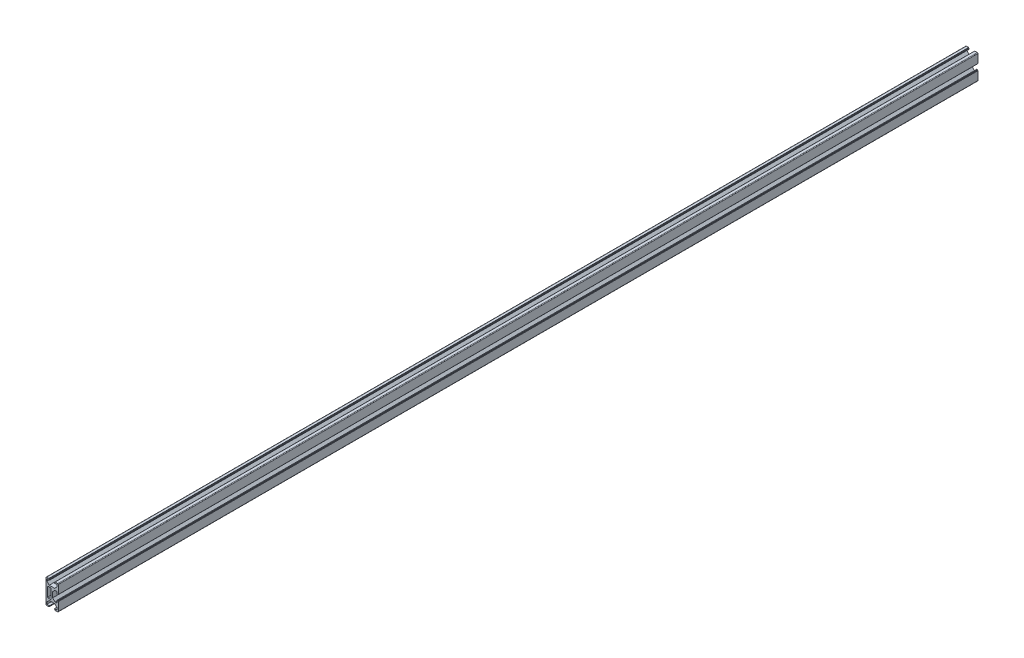
SolidWorks part; units mm, degrees
ref_plane "前视基准面" through (0, 0, 0) normal (0, 0, 1) x (1, 0, 0)
ref_plane "上视基准面" through (0, 0, 0) normal (0, 1, 0) x (1, 0, 0)
ref_plane "右视基准面" through (0, 0, 0) normal (1, 0, 0) x (0, 0, -1)
sketch "草图30" plane through (0, 0, 0) normal (0, 0, 1) x (1, 0, 0)
  line L0 (-10, 8.9627) -> (10, 8.9627) construction
  point P2 (0, 8.9627)
  line B0 (-1.7, 7.3) -> (-1.7, -7.3)
  line B1 (-2.7, -8.3) -> (-6.5, -8.3)
  line B2 (-7.5, -7.3) -> (-7.5, 7.3)
  line B3 (-6.5, 8.3) -> (-2.7, 8.3)
  line B4 (0.8, 4.3858) -> (4.6642, 8.25)
  line B5 (4.6642, 8.25) -> (8, 8.25)
  line B6 (8, 8.25) -> (8, 4.1)
  line B7 (8, 4.1) -> (9.2, 4.1)
  line B8 (9.2, 4.1) -> (9.2, 5.1)
  line B9 (9.2, 5.1) -> (10, 5.1)
  line B10 (10, 5.1) -> (10, 19)
  line B11 (9, 20) -> (4.8784, 20)
  line B12 (4.8784, 20) -> (4.8784, 19.2)
  line B13 (4.8784, 19.2) -> (3.8784, 19.2)
  line B14 (3.8784, 19.2) -> (3.8784, 18)
  line B15 (3.8784, 18) -> (8.0284, 18)
  line B16 (8.0284, 18) -> (8.0284, 14.6642)
  line B17 (8.0284, 14.6642) -> (4.1642, 10.8)
  line B18 (4.1642, 10.8) -> (-4.6074, 10.8)
  line B19 (-4.6074, 10.8) -> (-8.4716, 14.6642)
  line B20 (-8.4716, 14.6642) -> (-8.4716, 18)
  line B21 (-8.4716, 18) -> (-4.3216, 18)
  line B22 (-4.3216, 18) -> (-4.3216, 19.2)
  line B23 (-4.3216, 19.2) -> (-5.3216, 19.2)
  line B24 (-5.3216, 19.2) -> (-5.3216, 20)
  line B25 (-5.3216, 20) -> (-9, 20)
  line B26 (-10, 19) -> (-10, -19)
  line B27 (-9, -20) -> (-5.3216, -20)
  line B28 (-5.3216, -20) -> (-5.3216, -19.2)
  line B29 (-5.3216, -19.2) -> (-4.3216, -19.2)
  line B30 (-4.3216, -19.2) -> (-4.3216, -18)
  line B31 (-4.3216, -18) -> (-8.4716, -18)
  line B32 (-8.4716, -18) -> (-8.4716, -14.6642)
  line B33 (-8.4716, -14.6642) -> (-4.6074, -10.8)
  line B34 (-4.6074, -10.8) -> (4.1642, -10.8)
  line B35 (4.1642, -10.8) -> (8.0284, -14.6642)
  line B36 (8.0284, -14.6642) -> (8.0284, -18)
  line B37 (8.0284, -18) -> (3.8784, -18)
  line B38 (3.8784, -18) -> (3.8784, -19.2)
  line B39 (3.8784, -19.2) -> (4.8784, -19.2)
  line B40 (4.8784, -19.2) -> (4.8784, -20)
  line B41 (4.8784, -20) -> (9, -20)
  line B42 (10, -19) -> (10, -5.1)
  line B43 (10, -5.1) -> (9.2, -5.1)
  line B44 (9.2, -5.1) -> (9.2, -4.1)
  line B45 (9.2, -4.1) -> (8, -4.1)
  line B46 (8, -4.1) -> (8, -8.25)
  line B47 (8, -8.25) -> (4.6642, -8.25)
  line B48 (4.6642, -8.25) -> (0.8, -4.3858)
  line B49 (0.8, -4.3858) -> (0.8, 4.3858)
  arc B50 (-1.7, 7.3) -> (-2.7, 8.3) centre (-2.7, 7.3) ccw
  arc B51 (-2.7, -8.3) -> (-1.7, -7.3) centre (-2.7, -7.3) ccw
  arc B52 (-7.5, -7.3) -> (-6.5, -8.3) centre (-6.5, -7.3) ccw
  arc B53 (-6.5, 8.3) -> (-7.5, 7.3) centre (-6.5, 7.3) ccw
  arc B54 (10, 19) -> (9, 20) centre (9, 19) ccw
  arc B55 (-9, 20) -> (-10, 19) centre (-9, 19) ccw
  arc B56 (-10, -19) -> (-9, -20) centre (-9, -19) ccw
  arc B57 (9, -20) -> (10, -19) centre (9, -19) ccw
sketch_block_instance "块2-1"
sketch_block "块2"
extrude "凸台-拉伸3" add sketch "草图30" along normal blind 1500
ref_plane "基准面1" through (0, 0, 50) normal (0, 0, 1) x (1, 0, 0)
ref_plane "基准面2" through (0, 20, 0) normal (0, 1, 0) x (1, 0, 0)
ref_plane "基准面3" through (0, -20, 0) normal (0, 1, 0) x (1, 0, 0)
ref_plane "基准面4" through (10, 0, 0) normal (1, 0, 0) x (0, 0, -1)
ref_plane "基准面5" through (-10, 0, 0) normal (1, 0, 0) x (0, 0, -1)
sketch "草图19" plane through (0, 0, 0) normal (0, 0, 1) x (1, 0, 0)
  line L0 (0, 0) -> (0, 11.6901) construction
  line L1 (0, 0) -> (10.3437, 0) construction
sketch "草图20" plane through (0, 0, 0) normal (0, 1, 0) x (1, 0, 0)
  line L0 (0, 0) -> (0, 3.5576) construction
ref_point "点1"
sketch "草图2" [suppressed] plane through (0, 0, 0) normal (1, 0, 0) x (0, 0, -1)
  line L0 (-370, -20) -> (-330, 20)
  line L1 (11.189, -20) -> (-11.189, -20) construction
  line L2 (11.189, 20) -> (-11.189, 20) construction
  line L3 (-330, 20) -> (-370, 20)
  line L4 (-370, 11.189) -> (-370, -11.189) construction
  line L5 (-370, 20) -> (-370, -20)
  dimension "D1" = 45
extrude "切除-拉伸1" [suppressed] cut sketch "草图2" against normal through all and the other way through all
sketch "草图3" [suppressed] plane through (0, 0, 0) normal (1, 0, 0) x (0, 0, -1)
  line L0 (0, -20) -> (-40, 20)
  line L1 (11.189, -20) -> (-11.189, -20) construction
  line L2 (11.189, 20) -> (-11.189, 20) construction
  line L3 (-40, 20) -> (0, 20)
  line L4 (0, 20) -> (0, -20)
  line L5 (0, 11.189) -> (0, -11.189) construction
  dimension "D1" = 45
extrude "切除-拉伸2" [suppressed] cut sketch "草图3" against normal through all and the other way through all
sketch "草图4" [suppressed] plane through (0, 0, 0) normal (1, 0, 0) x (0, 0, -1)
  line L0 (-370, 20) -> (-330, -20)
  line L1 (11.189, 20) -> (-11.189, 20) construction
  line L2 (-370, 11.189) -> (-370, -11.189) construction
  line L3 (11.189, -20) -> (-11.189, -20) construction
  line L4 (-330, -20) -> (-370, -20)
  line L5 (-370, -20) -> (-370, 20)
  dimension "D1" = 45
extrude "切除-拉伸3" [suppressed] cut sketch "草图4" against normal through all and the other way through all
sketch "草图5" [suppressed] plane through (0, 0, 0) normal (1, 0, 0) x (0, 0, -1)
  line L0 (0, 20) -> (-40, -20)
  line L1 (11.189, 20) -> (-11.189, 20) construction
  line L2 (11.189, -20) -> (-11.189, -20) construction
  line L3 (-40, -20) -> (0, -20)
  line L4 (0, -20) -> (0, 20)
  line L5 (0, 11.189) -> (0, -11.189) construction
  dimension "D1" = 45
extrude "切除-拉伸4" [suppressed] cut sketch "草图5" against normal through all and the other way through all
sketch "草图6" [suppressed] plane through (0, 0, 0) normal (0, 1, 0) x (1, 0, 0)
  line L0 (-10, -370) -> (10, -350)
  line L1 (-10, -22) -> (-10, 22) construction
  line L2 (-11.189, -370) -> (11.189, -370) construction
  line L3 (10, -22) -> (10, 22) construction
  line L4 (10, -350) -> (10, -370)
  line L5 (10, -370) -> (-10, -370)
  dimension "D1" = 45
extrude "切除-拉伸5" [suppressed] cut sketch "草图6" against normal through all and the other way through all
sketch "草图7" [suppressed] plane through (0, 0, 0) normal (0, 1, 0) x (1, 0, 0)
  line L0 (-10, 0) -> (10, -20)
  line L1 (-10, -22) -> (-10, 22) construction
  line L2 (10, -22) -> (10, 22) construction
  line L3 (10, -20) -> (10, 0)
  line L4 (-11.189, 0) -> (11.189, 0) construction
  line L5 (10, 0) -> (-10, 0)
  dimension "D1" = 45
extrude "切除-拉伸6" [suppressed] cut sketch "草图7" against normal through all and the other way through all
sketch "草图8" [suppressed] plane through (0, 0, 0) normal (0, 1, 0) x (1, 0, 0)
  line L0 (-10, -350) -> (10, -370)
  line L1 (-10, -22) -> (-10, 22) construction
  line L2 (10, -22) -> (10, 22) construction
  line L3 (-11.189, -370) -> (11.189, -370) construction
  line L4 (10, -370) -> (-10, -370)
  line L5 (-10, -370) -> (-10, -350)
  dimension "D1" = 45
extrude "切除-拉伸7" [suppressed] cut sketch "草图8" against normal through all and the other way through all
sketch "草图9" [suppressed] plane through (0, 0, 0) normal (0, 1, 0) x (1, 0, 0)
  line L0 (10, 0) -> (-10, -20)
  line L1 (10, -22) -> (10, 22) construction
  line L2 (-11.189, 0) -> (11.189, 0) construction
  line L3 (-10, -22) -> (-10, 22) construction
  line L4 (-10, -20) -> (-10, 0)
  line L5 (-10, 0) -> (10, 0)
  dimension "D1" = 45
extrude "切除-拉伸8" [suppressed] cut sketch "草图9" against normal through all and the other way through all
sketch "草图18" [suppressed] plane through (0, 0, 0) normal (0, 1, 0) x (1, 0, 0)
  line L0 (-10, -307) -> (10, -307)
  line L1 (-10, -22) -> (-10, 22) construction
  line L2 (10, -22) -> (10, 22) construction
  line L3 (10, -307) -> (10, -300)
  line L4 (10, -300) -> (1.5, -300)
  line L5 (1.5, -300) -> (1.5, -302.5)
  line L6 (1.5, -302.5) -> (-10, -302.5)
  line L7 (-10, -302.5) -> (-10, -307)
  line L8 (-11.189, -370) -> (11.189, -370) construction
  dimension "D1" = 63
  dimension "D2" = 7
  dimension "D3" = 4.5
  dimension "D4" = 8.5
revolve "切除-旋转5" [suppressed] cut sketch "草图18" angle 360 about L0
other "表格阵列1" [suppressed] parameters "D0"=26, "D1"=0, "D2"=52, "D3"=0, "D4"=78, "D5"=0, "D6"=104, "D7"=0
sketch "草图21" [suppressed] plane through (0, 0, 0) normal (0, 1, 0) x (1, 0, 0)
  line L0 (-10, -63) -> (10, -63)
  line L1 (-10, -22) -> (-10, 22) construction
  line L2 (10, -22) -> (10, 22) construction
  line L3 (10, -63) -> (10, -70)
  line L4 (10, -70) -> (1.5, -70)
  line L5 (1.5, -70) -> (1.5, -67.5)
  line L6 (1.5, -67.5) -> (-10, -67.5)
  line L7 (-10, -67.5) -> (-10, -63)
  dimension "D1" = 7
  dimension "D2" = 4.5
  dimension "D3" = 8.5
  dimension "D4" = 63
revolve "切除-旋转6" [suppressed] cut sketch "草图21" angle 360 about L0
other "表格阵列2" [suppressed] parameters "D0"=26, "D1"=0, "D2"=52, "D3"=0, "D4"=78, "D5"=0, "D6"=104, "D7"=0
sketch "草图22" [suppressed] plane through (0, 0, 0) normal (1, 0, 0) x (0, 0, -1)
  line L0 (-307, 20) -> (-307, -20)
  line L1 (11.189, 20) -> (-11.189, 20) construction
  line L2 (11.189, -20) -> (-11.189, -20) construction
  line L3 (-307, -20) -> (-302.5, -20)
  line L4 (-302.5, -20) -> (-302.5, 11.5)
  line L5 (-302.5, 11.5) -> (-300, 11.5)
  line L6 (-300, 11.5) -> (-300, 20)
  line L7 (-300, 20) -> (-307, 20)
  line L8 (-370, 11.189) -> (-370, -11.189) construction
  dimension "D1" = 7
  dimension "D2" = 4.5
  dimension "D3" = 8.5
  dimension "D4" = 63
revolve "切除-旋转7" [suppressed] cut sketch "草图22" angle 360 about L0
other "表格阵列3" [suppressed] parameters "D0"=26, "D1"=0, "D2"=52, "D3"=0, "D4"=78, "D5"=0, "D6"=104, "D7"=0
sketch "草图23" [suppressed] plane through (0, 0, 0) normal (1, 0, 0) x (0, 0, -1)
  line L0 (-63, 20) -> (-70, 20)
  line L1 (11.189, 20) -> (-11.189, 20) construction
  line L2 (-70, 20) -> (-70, 11.5)
  line L3 (-70, 11.5) -> (-67.5, 11.5)
  line L4 (-67.5, 11.5) -> (-67.5, -20)
  line L5 (11.189, -20) -> (-11.189, -20) construction
  line L6 (-67.5, -20) -> (-63, -20)
  line L7 (-63, -20) -> (-63, 20)
  dimension "D1" = 7
  dimension "D2" = 4.5
  dimension "D3" = 8.5
  dimension "D4" = 63
revolve "切除-旋转8" [suppressed] cut sketch "草图23" angle 360 about L7
other "表格阵列4" [suppressed] parameters "D0"=26, "D1"=0, "D2"=52, "D3"=0, "D4"=78, "D5"=0, "D6"=104, "D7"=0
sketch "草图24" [suppressed] plane through (10, 0, 0) normal (1, 0, 0) x (0, 0, -1)
  line L0 (-370, 11.189) -> (-370, -11.189) construction
  circle A0 centre (-320, 0) radius 4.25
  dimension "D1" = 8.5
  dimension "D2" = 50
extrude "切除-拉伸13" [suppressed] cut sketch "草图24" against normal through all
other "表格阵列5" [suppressed] parameters "D0"=26, "D1"=0, "D2"=52, "D3"=0, "D4"=78, "D5"=0, "D6"=104, "D7"=0
sketch "草图25" [suppressed] plane through (10, 0, 0) normal (1, 0, 0) x (0, 0, -1)
  circle A0 centre (-50, 0) radius 4.25
  dimension "D1" = 8.5
  dimension "D2" = 50
extrude "切除-拉伸14" [suppressed] cut sketch "草图25" against normal through all
other "表格阵列6" [suppressed] parameters "D0"=26, "D1"=0, "D2"=52, "D3"=0, "D4"=78, "D5"=0, "D6"=104, "D7"=0
sketch "草图26" [suppressed] plane through (0, 20, 0) normal (0, 1, 0) x (1, 0, 0)
  line L0 (-11.189, -370) -> (11.189, -370) construction
  circle A0 centre (0, -320) radius 4.25
  dimension "D1" = 8.5
  dimension "D2" = 50
extrude "切除-拉伸15" [suppressed] cut sketch "草图26" against normal through all
other "表格阵列7" [suppressed] parameters "D0"=26, "D1"=0, "D2"=52, "D3"=0, "D4"=78, "D5"=0, "D6"=104, "D7"=0
sketch "草图27" [suppressed] plane through (0, 20, 0) normal (0, 1, 0) x (1, 0, 0)
  circle A0 centre (0, -50) radius 4.25
  dimension "D1" = 8.5
  dimension "D2" = 50
extrude "切除-拉伸16" [suppressed] cut sketch "草图27" against normal through all
other "表格阵列8" [suppressed] parameters "D0"=26, "D1"=0, "D2"=52, "D3"=0, "D4"=78, "D5"=0, "D6"=104, "D7"=0
sketch "草图31" [suppressed] plane through (0, 0, 0) normal (0, 1, 0) x (1, 0, 0)
  line L0 (-10, -307) -> (-10, -300)
  line L1 (-10, -300) -> (-1.5, -300)
  line L2 (-1.5, -300) -> (-1.5, -302.5)
  line L3 (-1.5, -302.5) -> (10, -302.5)
  line L4 (10, -302.5) -> (10, -307)
  line L5 (10, -307) -> (-10, -307)
  line L6 (-10, -22) -> (-10, 22) construction
  line L7 (10, -22) -> (10, 22) construction
  line L8 (-11.189, -370) -> (11.189, -370) construction
  dimension "D1" = 4.5
  dimension "D2" = 7
  dimension "D3" = 8.5
  dimension "D4" = 63
revolve "切除-旋转9" [suppressed] cut sketch "草图31" angle 360 about L5
other "表格阵列9" [suppressed] parameters "D0"=26, "D1"=0, "D2"=52, "D3"=0, "D4"=78, "D5"=0, "D6"=104, "D7"=0
sketch "草图32" [suppressed] plane through (0, 0, 0) normal (0, 1, 0) x (1, 0, 0)
  line L0 (10, -63) -> (10, -67.5)
  line L1 (10, -67.5) -> (-1.5, -67.5)
  line L2 (-1.5, -67.5) -> (-1.5, -70)
  line L3 (-1.5, -70) -> (-10, -70)
  line L4 (-10, -70) -> (-10, -63)
  line L5 (-10, -63) -> (10, -63)
  line L6 (-10, -22) -> (-10, 22) construction
  line L7 (10, -22) -> (10, 22) construction
  dimension "D1" = 7
  dimension "D2" = 8.5
  dimension "D3" = 4.5
  dimension "D4" = 63
revolve "切除-旋转10" [suppressed] cut sketch "草图32" angle 360 about L5
other "表格阵列10" [suppressed] parameters "D0"=26, "D1"=0, "D2"=52, "D3"=0, "D4"=78, "D5"=0, "D6"=104, "D7"=0
sketch "草图33" [suppressed] plane through (0, 0, 0) normal (1, 0, 0) x (0, 0, -1)
  line L0 (-307, 20) -> (-302.5, 20)
  line L1 (-302.5, 20) -> (-302.5, -11.5)
  line L2 (-302.5, -11.5) -> (-300, -11.5)
  line L3 (-300, -11.5) -> (-300, -20)
  line L4 (-300, -20) -> (-307, -20)
  line L5 (-307, -20) -> (-307, 20)
  line L6 (11.189, -20) -> (-11.189, -20) construction
  line L7 (11.189, 20) -> (-11.189, 20) construction
  line L8 (-370, 11.189) -> (-370, -11.189) construction
  dimension "D1" = 4.5
  dimension "D2" = 7
  dimension "D3" = 8.5
  dimension "D4" = 63
revolve "切除-旋转11" [suppressed] cut sketch "草图33" angle 360 about L5
other "表格阵列11" [suppressed] parameters "D0"=26, "D1"=0, "D2"=52, "D3"=0, "D4"=78, "D5"=0, "D6"=104, "D7"=0
sketch "草图34" [suppressed] plane through (0, 0, 0) normal (1, 0, 0) x (0, 0, -1)
  line L0 (-63, 20) -> (-67.5, 20)
  line L1 (-67.5, 20) -> (-67.5, -11.5)
  line L2 (-67.5, -11.5) -> (-70, -11.5)
  line L3 (-70, -11.5) -> (-70, -20)
  line L4 (-70, -20) -> (-63, -20)
  line L5 (-63, -20) -> (-63, 20)
  line L6 (11.189, -20) -> (-11.189, -20) construction
  line L7 (11.189, 20) -> (-11.189, 20) construction
  dimension "D1" = 4.5
  dimension "D2" = 7
  dimension "D3" = 8.5
  dimension "D4" = 63
revolve "切除-旋转12" [suppressed] cut sketch "草图34" angle 360 about L5
other "表格阵列13" [suppressed] parameters "D0"=26, "D1"=0, "D2"=52, "D3"=0, "D4"=78, "D5"=0, "D6"=104, "D7"=0
equation "\"L\"= 1500"
equation "\"D1@凸台-拉伸3\"=\"L\""
